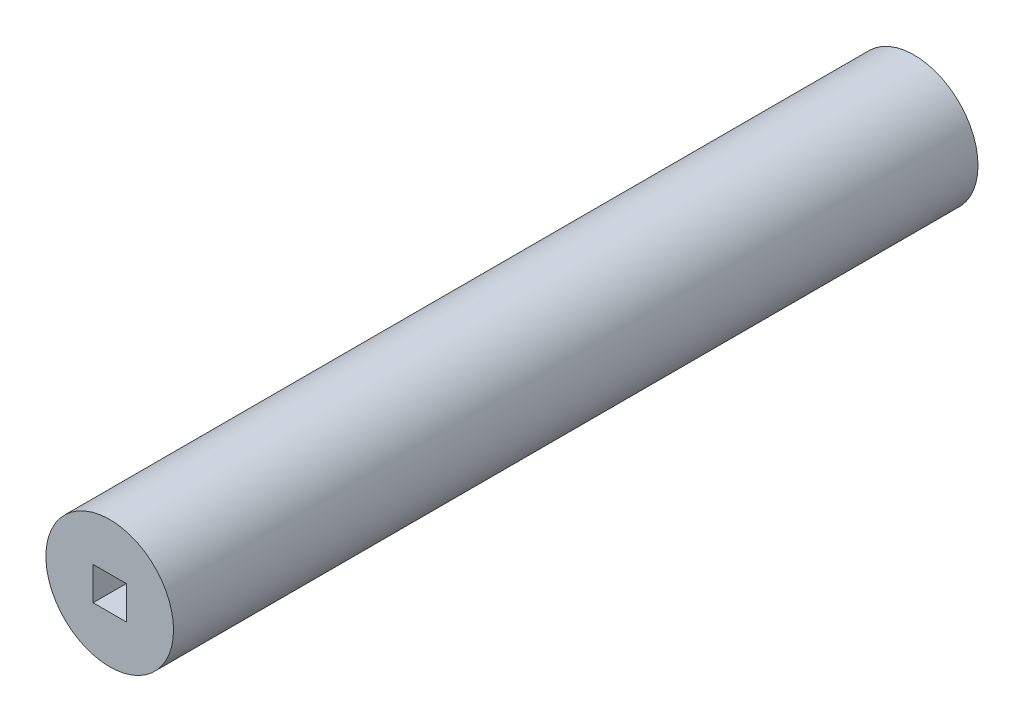
SolidWorks part; units mm, degrees
ref_plane "Plan de face" through (0, 0, 0) normal (0, 0, 1) x (1, 0, 0)
ref_plane "Plan de dessus" through (0, 0, 0) normal (0, 1, 0) x (1, 0, 0)
ref_plane "Plan de droite" through (0, 0, 0) normal (1, 0, 0) x (0, 0, -1)
sketch "Esquisse1" plane through (0, 0, 0) normal (0, 0, 1) x (1, 0, 0)
  circle A0 centre (0, 0) radius 5.95
  dimension "D1" = 11.9
extrude "Boss.-Extru.1" add sketch "Esquisse1" along normal blind 75
sketch "Esquisse2" plane through (0, 0, 0) normal (0, 0, -1) x (-1, 0, 0)
  line L1 (-1.55, -1.55) -> (1.55, -1.55)
  line L2 (-1.55, -1.55) -> (-1.55, 1.55)
  line L3 (-1.55, 1.55) -> (1.55, 1.55)
  line L4 (1.55, -1.55) -> (1.55, 1.55)
  line L5 (-1.55, -1.55) -> (1.55, 1.55) construction
  line L6 (-1.55, 1.55) -> (1.55, -1.55) construction
  point P0 (0, 0)
  dimension "D1" = 3.1
  dimension "D2" = 3.1
extrude "Enlèv. mat.-Extru.1" cut sketch "Esquisse2" against normal through all
equation "\"D2@Esquisse2\"=\"D1@Esquisse2\""
